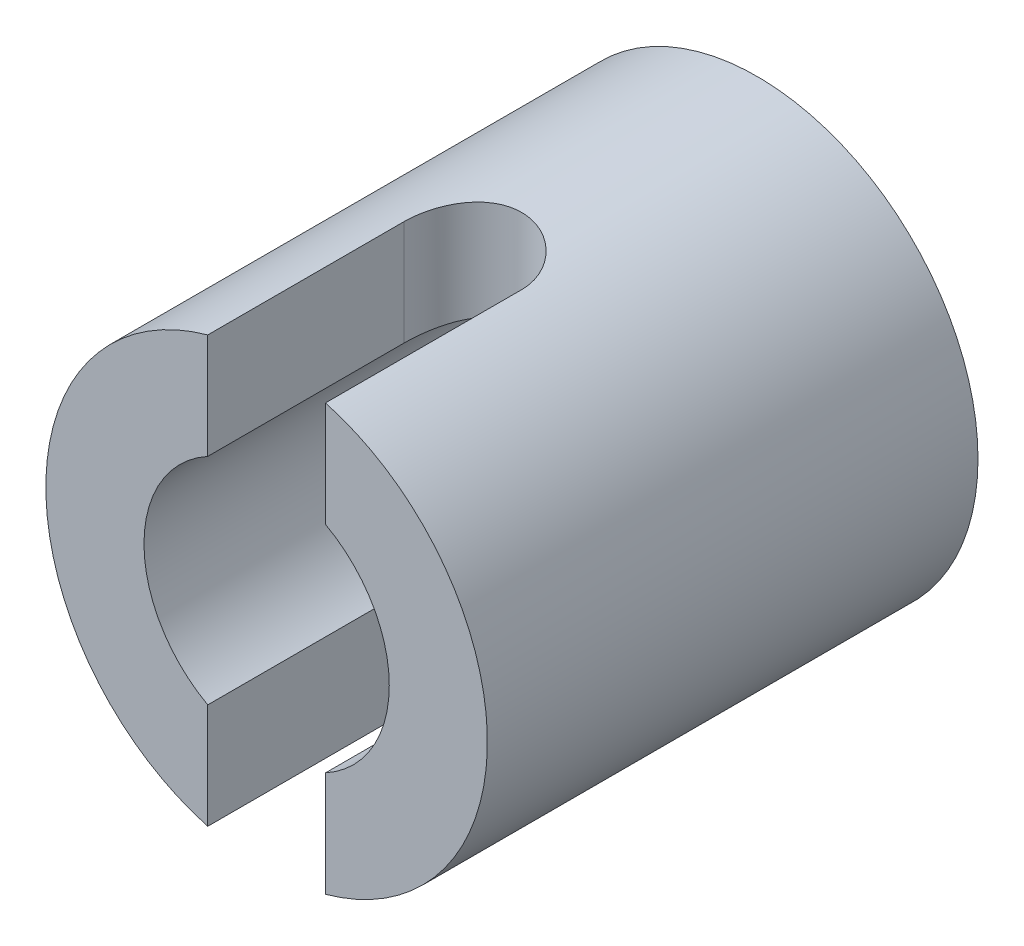
SolidWorks part; units mm, degrees
ref_plane "Front Plane" through (0, 0, 0) normal (0, 0, 1) x (1, 0, 0)
ref_plane "Top Plane" through (0, 0, 0) normal (0, 1, 0) x (1, 0, 0)
ref_plane "Right Plane" through (0, 0, 0) normal (1, 0, 0) x (0, 0, -1)
sketch "Sketch1" plane through (0, 0, 0) normal (0, 0, 1) x (1, 0, 0)
  circle A0 centre (0, 0) radius 22.5
  circle A1 centre (0, 0) radius 12.5
  dimension "D1" = 45
  dimension "D2" = 25
extrude "Boss-Extrude1" add sketch "Sketch1" along normal blind 50 contours A0 A1
sketch "Sketch2" plane through (0, 0, 0) normal (0, 1, 0) x (1, 0, 0)
  line L0 (0, -30) -> (0, -50) construction
  line L1 (6, -30) -> (6, -50)
  line L2 (-6, -30) -> (-6, -50)
  line L3 (-22.5, -50) -> (22.5, -50) construction
  arc A0 (6, -30) -> (-6, -30) centre (0, -30) ccw
  arc A1 (-6, -50) -> (6, -50) centre (0, -50) ccw
  point P3 (0, -40)
  point P8 (0, 0)
  point P9 (0, 0)
  dimension "D2" = 6
  dimension "D1" = 20
extrude "Cut-Extrude1" cut sketch "Sketch2" against normal through all both and the other way through all
